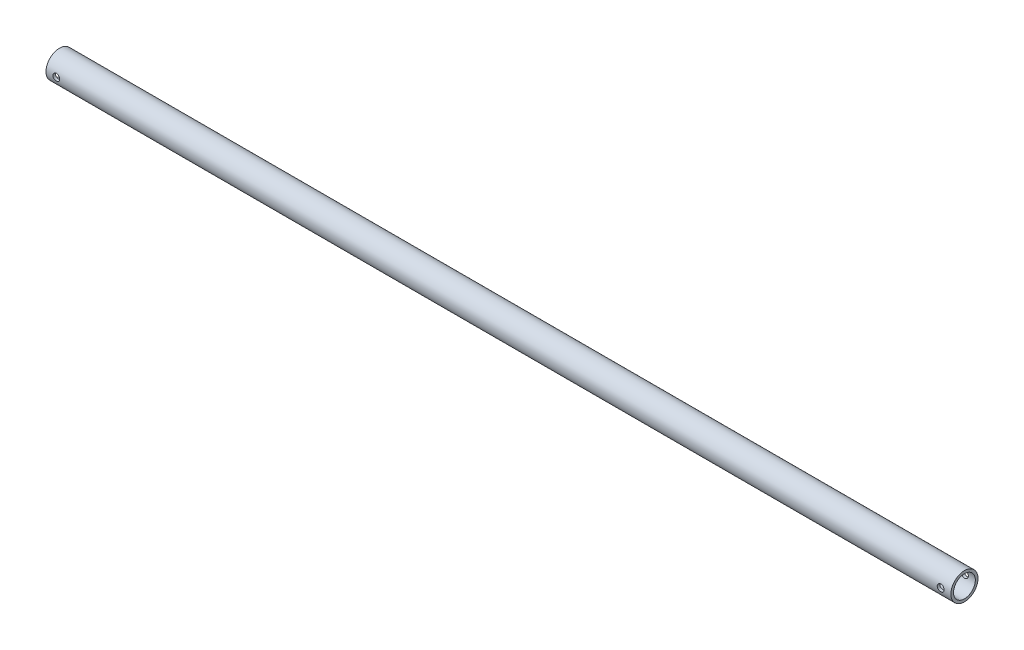
SolidWorks part; units mm, degrees
ref_plane "Front Plane" through (0, 0, 0) normal (0, 0, 1) x (1, 0, 0)
ref_plane "Top Plane" through (0, 0, 0) normal (0, 1, 0) x (1, 0, 0)
ref_plane "Right Plane" through (0, 0, 0) normal (1, 0, 0) x (0, 0, -1)
sketch "Sketch1" plane through (0, 0, 0) normal (1, 0, 0) x (0, 0, -1)
  circle A0 centre (0, 0) radius 6.35
  circle A1 centre (0, 0) radius 5.1054
  dimension "D1" = 12.7
  dimension "D2" = 10.2108
extrude "Boss-Extrude1" add sketch "Sketch1" along normal blind 424.1241
sketch "Sketch2" plane through (0, 0, 0) normal (0, 0, 1) x (1, 0, 0)
  line L0 (424.1241, 6.35) -> (0, 6.35) construction
  line L1 (424.1241, -6.35) -> (424.1241, 6.35) construction
  circle A0 centre (4.826, 0) radius 1.5875
  circle A1 centre (419.2981, 0) radius 1.5875
  point P9 (0, 0)
  dimension "D1" = 4.826
  dimension "D2" = 3.175
  dimension "D4" = 3.175
  dimension "D3" = 6.35
  dimension "D5" = 4.826
  dimension "D6" = 6.35
extrude "Cut-Extrude1" cut sketch "Sketch2" against normal through all and the other way through all
